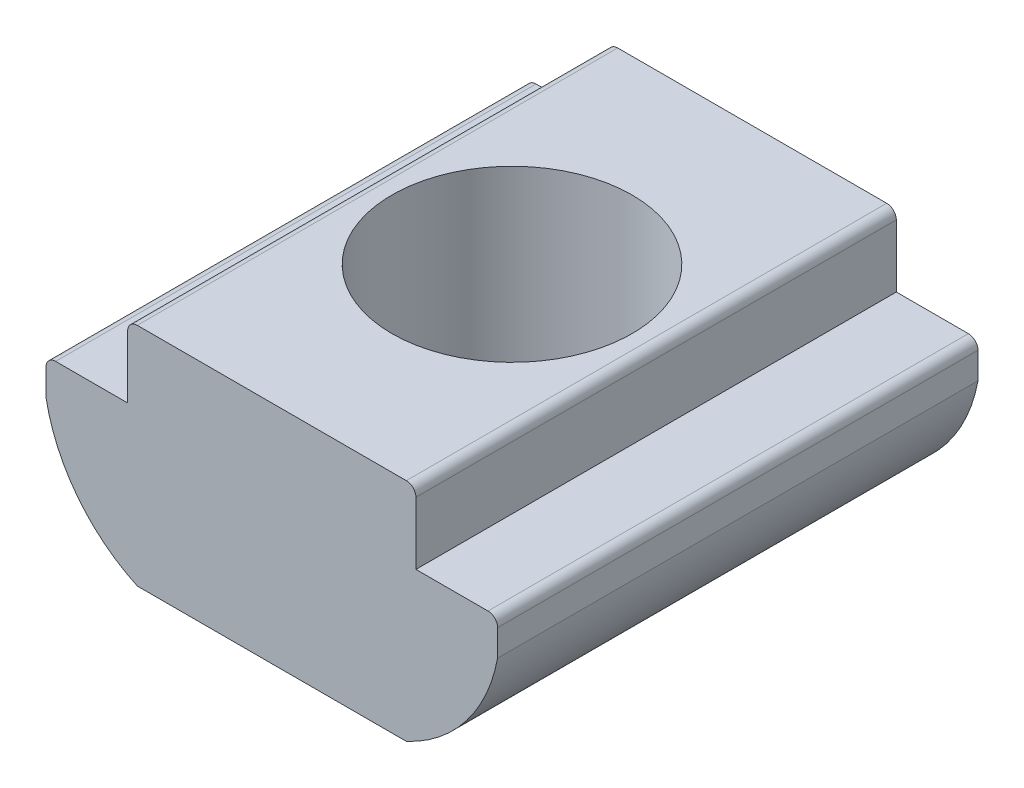
SolidWorks part; units mm, degrees
ref_plane "前视基准面" through (0, 0, 0) normal (0, 0, 1) x (1, 0, 0)
ref_plane "上视基准面" through (0, 0, 0) normal (0, 1, 0) x (1, 0, 0)
ref_plane "右视基准面" through (0, 0, 0) normal (1, 0, 0) x (0, 0, -1)
sketch "草图1" plane through (0, 0, 0) normal (0, 0, 1) x (1, 0, 0)
  line B0 (-2.8, 4.7) -> (2.8, 4.7)
  line B1 (4.7, 3) -> (4.7, 2.45)
  line B2 (-4.7, 3) -> (-4.7, 2.45)
  line B3 (-2.8, 0) -> (2.8, 0)
  line B4 (-4.5, 3.2) -> (-3, 3.2)
  line B5 (3, 3.2) -> (4.5, 3.2)
  line B6 (-3, 4.5) -> (-3, 3.2)
  line B7 (3, 4.5) -> (3, 3.2)
  arc B8 (-2.8, 4.7) -> (-3, 4.5) centre (-2.8, 4.5) ccw
  arc B9 (3, 4.5) -> (2.8, 4.7) centre (2.8, 4.5) ccw
  arc B10 (-4.5, 3.2) -> (-4.7, 3) centre (-4.5, 3) ccw
  arc B11 (4.7, 3) -> (4.5, 3.2) centre (4.5, 3) ccw
  arc B12 (-4.7, 2.45) -> (-2.8, 0) centre (-1.3774, 3.0649) ccw
  arc B13 (2.8, 0) -> (4.7, 2.45) centre (1.3774, 3.0649) ccw
sketch_block_instance "A$C334B3D09-1"
sketch_block "A$C334B3D09"
extrude "凸台-拉伸1" add sketch "草图1" along normal mid plane 10
sketch "草图3" plane through (0, 4.7, 0) normal (0, 1, 0) x (1, 0, 0)
  point P0 (0, 0)
hole_wizard "M6 螺纹孔1" positions "3D草图1" profile "草图4" tap size "M6" standard "Iso"
sketch3d "3D草图1"
  point P0 (0, 4.7, 0)
sketch "草图4" plane through (0, 4.7, 0) normal (1, 0, 0) x (0, 0, 1)
  line L0 (0, 0) -> (0, 16.5022)
  line L1 (0, 16.5022) -> (2.5, 15)
  line L2 (2.5, 15) -> (2.5, 0)
  line L5 (2.5, 0) -> (0, 0)
  line L10 (0, 16.5022) -> (-2.5, 15) construction
  line L11 (0, -6.35) -> (0, 107.95) construction
  dimension "螺纹孔钻头直径" = 5
  dimension "螺纹孔钻头深度" = 15
  dimension "导头角度" = 118
cosmetic thread "孔螺蚊线1" parameters "D1"=4.7, "D2"=6
